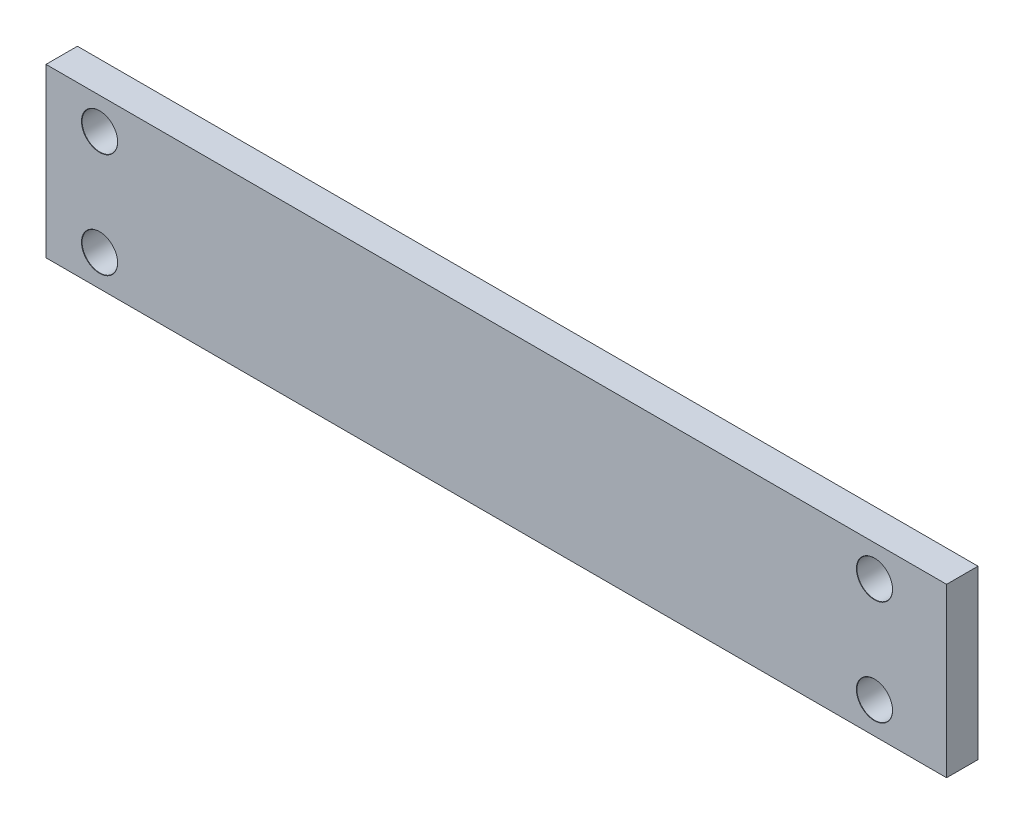
SolidWorks part; units mm, degrees
ref_plane "Front Plane" through (0, 0, 0) normal (0, 0, 1) x (1, 0, 0)
ref_plane "Top Plane" through (0, 0, 0) normal (0, 1, 0) x (1, 0, 0)
ref_plane "Right Plane" through (0, 0, 0) normal (1, 0, 0) x (0, 0, -1)
sketch "Sketch1" plane through (0, 0, 0) normal (0, 0, 1) x (1, 0, 0)
  line L1 (0, 0) -> (86, 0)
  line L2 (0, 0) -> (0, 16)
  line L3 (0, 16) -> (86, 16)
  line L4 (86, 0) -> (86, 16)
  dimension "D1" = 86
  dimension "D2" = 16
extrude "Boss-Extrude1" add sketch "Sketch1" along normal blind 3
sketch "Sketch4" plane through (0, 0, 3) normal (0, 0, 1) x (1, 0, 0)
  line L0 (5.1158, 3) -> (5.1158, 13)
  line L1 (5.1158, 13) -> (79.1158, 13)
  line L2 (79.1158, 3) -> (79.1158, 13)
  line L4 (5.1158, 8) -> (0, 8) construction
  line L5 (0, 16) -> (0, 0) construction
  point P0 (5.1158, 13)
  point P2 (5.1158, 3)
  point P4 (79.1158, 13)
  point P6 (79.1158, 3)
  dimension "D1" = 74
  dimension "D2" = 10
hole_wizard "M3 Clearance Hole1" positions "Sketch4" profile "Sketch3" hole size "M3" standard "DIN" end condition through all
sketch "Sketch3" plane through (5.1158, 13, 3) normal (1, 0, 0) x (0, -1, 0)
  line L0 (0, 0) -> (0, 3)
  line L1 (0, 3) -> (1.7, 3)
  line L2 (1.7, 3) -> (1.7, 0.025)
  line L3 (1.7, 0.025) -> (1.725, 0)
  line L5 (1.725, 0) -> (0, 0)
  line L6 (-1.7, 0.025) -> (-1.725, 0) construction
  line L11 (0, -6.35) -> (0, 107.95) construction
  dimension "Thru Hole Dia." = 3.4
  dimension "Thru Hole Depth" = 3
  dimension "Near C'Sink Dia." = 3.45
  dimension "Near C'Sink Angle" = 90
